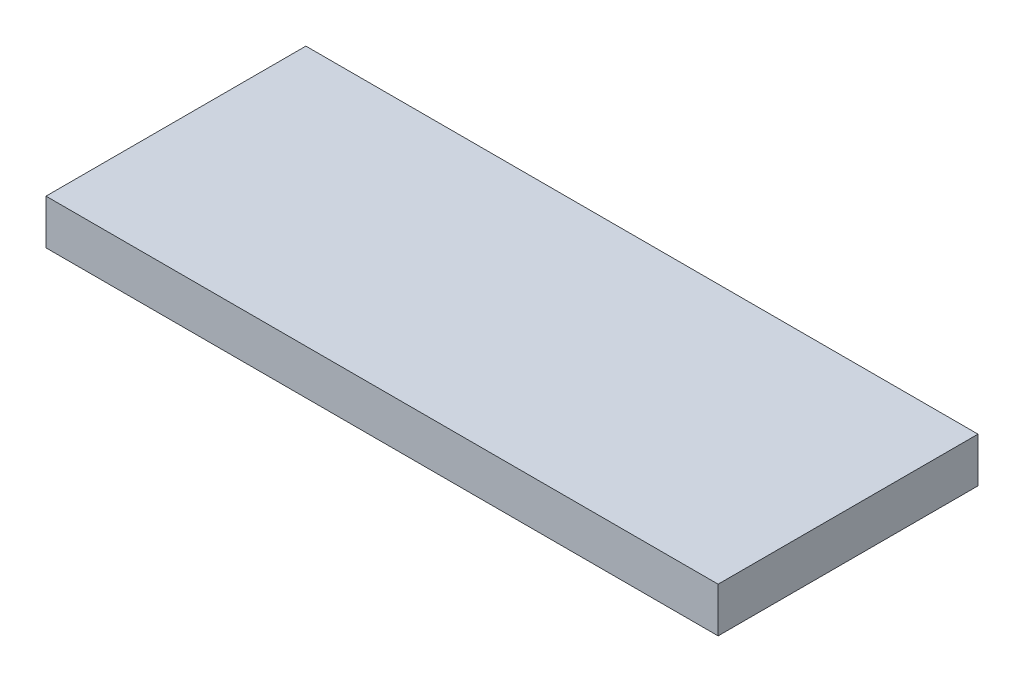
SolidWorks part; units mm, degrees
ref_plane "前视基准面" through (0, 0, 0) normal (0, 0, 1) x (1, 0, 0)
ref_plane "上视基准面" through (0, 0, 0) normal (0, 1, 0) x (1, 0, 0)
ref_plane "右视基准面" through (0, 0, 0) normal (1, 0, 0) x (0, 0, -1)
sketch "草图1" plane through (0, 0, 0) normal (0, 1, 0) x (1, 0, 0)
  line L1 (0, 0) -> (75, 0)
  line L2 (0, 0) -> (0, 29)
  line L3 (0, 29) -> (75, 29)
  line L4 (75, 0) -> (75, 29)
  dimension "D1" = 75
  dimension "D2" = 29
extrude "凸台-拉伸1" add sketch "草图1" along normal blind 5
